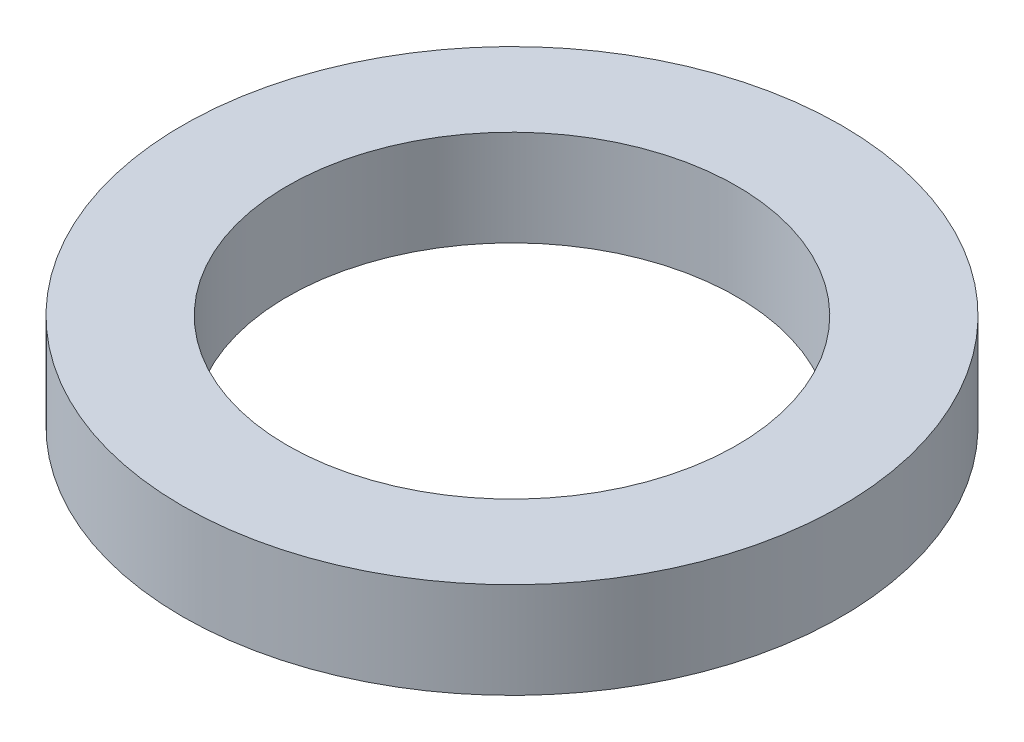
SolidWorks part; units mm, degrees
ref_plane "Front Plane" through (0, 0, 0) normal (0, 0, 1) x (1, 0, 0)
ref_plane "Top Plane" through (0, 0, 0) normal (0, 1, 0) x (1, 0, 0)
ref_plane "Right Plane" through (0, 0, 0) normal (1, 0, 0) x (0, 0, -1)
sketch "Sketch1" plane through (0, 0, 0) normal (0, 1, 0) x (1, 0, 0)
  circle A0 centre (0, 0) radius 37.5
  circle A1 centre (0, 0) radius 55
  dimension "D1" = 75
  dimension "D2" = 110
extrude "Boss-Extrude1" add sketch "Sketch1" along normal blind 16
